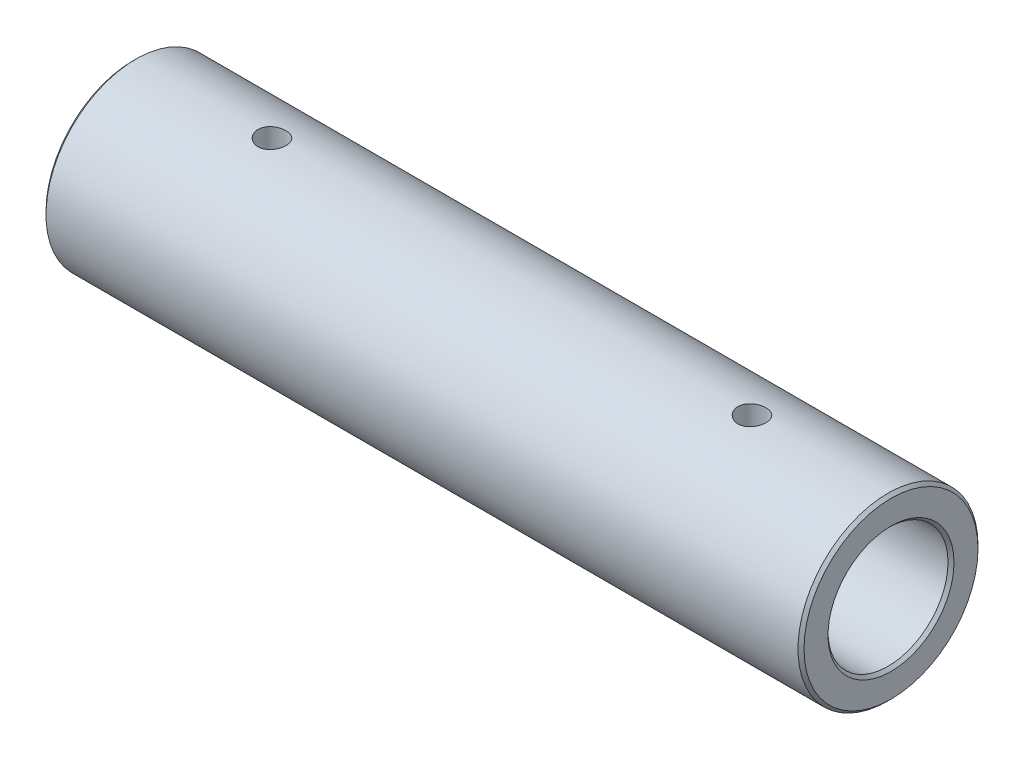
SolidWorks part; units mm, degrees
material "20"
ref_plane "前视基准面" through (0, 0, 0) normal (0, 0, 1) x (1, 0, 0)
ref_plane "上视基准面" through (0, 0, 0) normal (0, 1, 0) x (1, 0, 0)
ref_plane "右视基准面" through (0, 0, 0) normal (1, 0, 0) x (0, 0, -1)
sketch "草图1" plane through (0, 0, 0) normal (1, 0, 0) x (0, 0, -1)
  circle A0 centre (0, 0) radius 45
  circle A1 centre (0, 0) radius 30
  dimension "D1" = 90
  dimension "D2" = 60
extrude "凸台-拉伸1" add sketch "草图1" along normal blind 379
chamfer "倒角1" distance 1.5 angle 45 4 edges at (379, 0, -30) (379, 0, -45) (0, 0, -30) (0, 0, -45)
ref_plane "基准面1" through (0, 45, 0) normal (0, 1, 0) x (1, 0, 0)
hole_wizard "M16 螺纹孔2" positions "草图9" profile "草图10" tap size "M16" standard "GB"
sketch "草图9" plane through (0, 45, 0) normal (0, 1, 0) x (1, 0, 0)
  line L0 (189.5, 45) -> (189.5, -45) construction
  line L1 (377.5, 45) -> (1.5, 45) construction
  line L2 (1.5, -45) -> (377.5, -45) construction
  line L4 (377.5, 45) -> (1.5, 45) construction
  point P0 (69.5, 0)
  point P2 (309.5, 0)
  dimension "D1" = 240
  dimension "D2" = 45
sketch "草图10" plane through (69.5, 45, 0) normal (1, 0, 0) x (0, 0, 1)
  line L0 (0, 0) -> (0, 46.206)
  line L1 (0, 46.206) -> (7, 42)
  line L2 (7, 42) -> (7, 0)
  line L5 (7, 0) -> (0, 0)
  line L10 (0, 46.206) -> (-7, 42) construction
  line L11 (0, -6.35) -> (0, 107.95) construction
  dimension "螺纹孔钻头直径" = 14
  dimension "螺纹孔钻头深度" = 42
  dimension "导头角度" = 118
cosmetic thread "孔螺蚊线1"
cosmetic thread "孔螺蚊线2"
